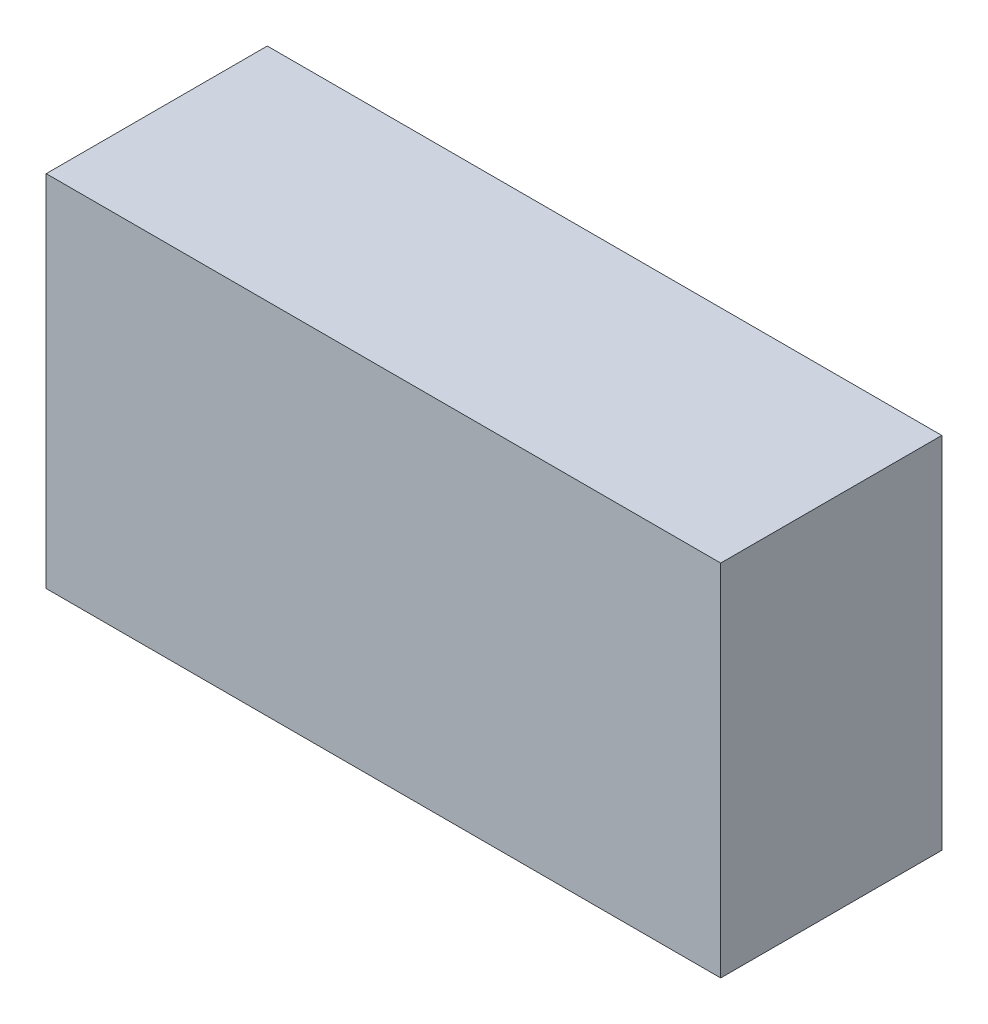
SolidWorks part; units mm, degrees
ref_plane "Front Plane" through (0, 0, 0) normal (0, 0, 1) x (1, 0, 0)
ref_plane "Top Plane" through (0, 0, 0) normal (0, 1, 0) x (1, 0, 0)
ref_plane "Right Plane" through (0, 0, 0) normal (1, 0, 0) x (0, 0, -1)
sketch "Sketch1" plane through (0, 0, 0) normal (0, 0, 1) x (1, 0, 0)
  line L0 (-1.5254, 0.8254) -> (1.5254, 0.8254)
  line L1 (1.5254, 0.8254) -> (1.5254, -0.8)
  line L2 (1.5254, -0.8) -> (-1.5254, -0.8)
  line L3 (-1.5254, -0.8) -> (-1.5254, 0.8254)
extrude "Component_Outline" add sketch "Sketch1" along normal blind 1 separate body
sketch3d "3DSketch1"
  line L0 (0, 0, 0) -> (1, 0, 0)
  line L1 (0, 0, 0) -> (0, 1, 0)
  line L2 (0, 0, 0) -> (0, 0, 1)
  point P0 (0, 0, 0)
